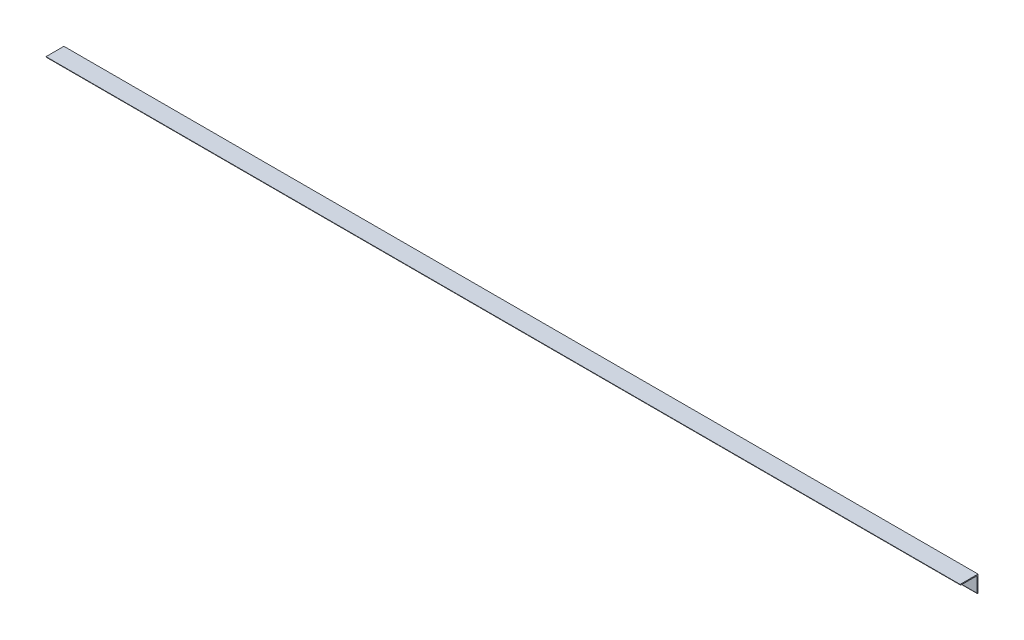
SolidWorks part; units mm, degrees
ref_plane "Front Plane" through (0, 0, 0) normal (0, 0, 1) x (1, 0, 0)
ref_plane "Top Plane" through (0, 0, 0) normal (0, 1, 0) x (1, 0, 0)
ref_plane "Right Plane" through (0, 0, 0) normal (1, 0, 0) x (0, 0, -1)
sketch "Sketch1" plane through (0, 0, 0) normal (0, 0, 1) x (1, 0, 0)
  line L0 (0, 0) -> (-4595, 0)
  dimension "D1" = 4595
other "Angle iron 35 X 35 X 5(2)"
ref_plane "Plane2" through (0, 0, 0) normal (-1, 0, 0) x (0, -1, 0)
sketch "Sketch13" plane through (0, 0, 0) normal (-1, 0, 0) x (0, -1, 0)
  line L0 (0, 0) -> (0, 90)
  line L1 (0, 45) -> (5, 45) construction
  line L2 (5, 85) -> (5, 10)
  line L3 (10, 5) -> (80, 5)
  line L4 (42.5, 5) -> (42.5, 0) construction
  line L5 (85, 0) -> (0, 0)
  arc A0 (85, 0) -> (80, 5) centre (80, 0) ccw
  arc A1 (0, 90) -> (5, 85) centre (0, 85) cw
  arc A2 (10, 5) -> (5, 10) centre (10, 10) cw
  point P10 (42.5, 0)
  point P14 (0, 45)
  point P15 (5, 45)
  point P16 (42.5, 5)
  point P17 (5, 90)
  point P18 (85, 5)
  point P21 (0, 0)
  dimension "D2" = 5
  dimension "D3" = 85
  dimension "Radius_1" = 5
  dimension "D1" = 5
  dimension "D4" = 90
